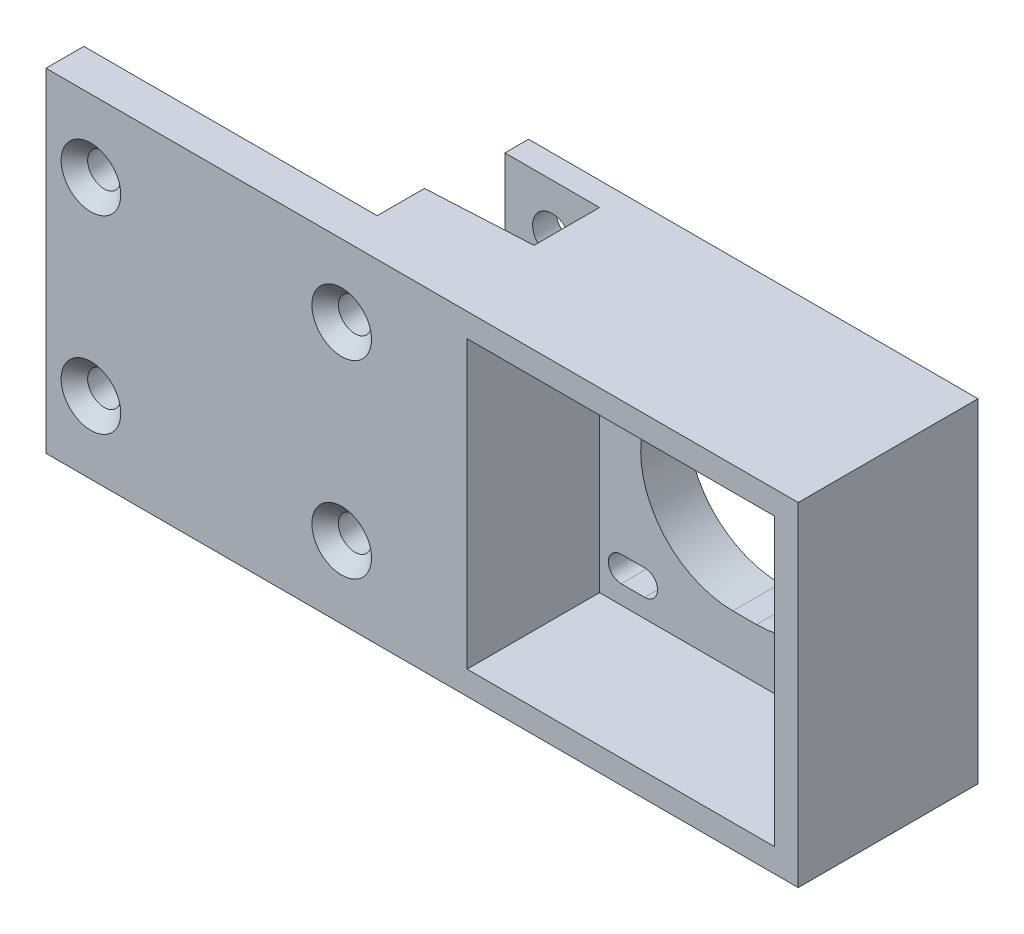
SolidWorks part; units mm, degrees
ref_plane "Front Plane" through (0, 0, 0) normal (0, 0, 1) x (1, 0, 0)
ref_plane "Top Plane" through (0, 0, 0) normal (0, 1, 0) x (1, 0, 0)
ref_plane "Right Plane" through (0, 0, 0) normal (1, 0, 0) x (0, 0, -1)
sketch "Sketch1" plane through (0, 0, 0) normal (0, 0, 1) x (1, 0, 0)
  line L1 (31, 106.401) -> (-31, 106.401) construction
  line L2 (31, 106.401) -> (31, 55.901) construction
  line L3 (31, 55.901) -> (-31, 55.901) construction
  line L4 (-31, 106.401) -> (-31, 55.901) construction
  line L5 (53, 116.401) -> (-36, 116.401)
  line L6 (53, 116.401) -> (53, 45.901)
  line L7 (53, 45.901) -> (-36, 45.901)
  line L8 (-36, 116.401) -> (-36, 45.901)
  circle A1 centre (26.5, 61.151) radius 2.5
  circle A2 centre (-26.5, 61.151) radius 2.5
  circle A3 centre (-26.5, 101.151) radius 2.5
  circle A4 centre (26.5, 101.151) radius 2.5
  dimension "D1" = 5
  dimension "D2" = 10
  dimension "D3" = 10
  dimension "D4" = 22
extrude "Boss-Extrude1" add sketch "Sketch1" along normal blind 8
sketch "Sketch2" plane through (53, 0, 0) normal (1, 0, 0) x (0, 0, -1)
  line L0 (-8, 45.901) -> (0, 45.901) construction
  line L1 (-8, 116.401) -> (30, 116.401)
  line L2 (-8, 116.401) -> (-8, 45.901)
  line L3 (-8, 45.901) -> (30, 45.901)
  line L4 (30, 116.401) -> (30, 45.901)
  dimension "D1" = 30
extrude "Boss-Extrude2" add sketch "Sketch2" against normal blind 5
sketch "Sketch3" plane through (0, 0, -30) normal (0, 0, -1) x (-1, 0, 0)
  line L0 (-48, 116.401) -> (-48, 45.901) construction
  line L1 (-53, 45.901) -> (-53, 116.401) construction
  line L2 (-48, 45.901) -> (-48, 116.401) construction
  line L3 (-48, 45.901) -> (-118, 45.901)
  line L4 (-48, 45.901) -> (-48, 116.401) construction
  line L5 (-48, 116.401) -> (-118, 116.401)
  line L6 (-118, 45.901) -> (-118, 116.401)
  line L7 (-53, 116.401) -> (36, 116.401) construction
  line L8 (-48, 116.401) -> (-28, 116.401)
  line L9 (-48, 116.401) -> (-48, 45.901) construction
  line L10 (-48, 45.901) -> (-28, 45.901)
  line L11 (-28, 116.401) -> (-28, 45.901)
  point P3 (-48, 81.151)
  point P7 (-48, 81.151)
  dimension "D2" = 65
  dimension "D3" = 20
extrude "Boss-Extrude3" add sketch "Sketch3" against normal blind 5
ref_plane "Plane1" through (0, 81.151, 0) normal (0, 1, 0) x (1, 0, 0)
sketch "Sketch17" plane through (0, 0, -25) normal (0, 0, 1) x (1, 0, 0)
  line L8 (118, 116.401) -> (53, 116.401)
  line L9 (118, 116.401) -> (53, 116.401)
  line L10 (53, 45.901) -> (118, 45.901)
  line L11 (53, 116.401) -> (53, 45.901)
  line L15 (53, 116.401) -> (53, 45.901)
  line L16 (53, 45.901) -> (118, 45.901)
  line L17 (118, 45.901) -> (118, 116.401)
  line L18 (118, 45.901) -> (118, 116.401)
  dimension "D1" = 0
extrude "Boss-Extrude6" add sketch "Sketch17" along normal blind 5
sketch "Sketch7" plane through (0, 0, -25) normal (0, 0, 1) x (1, 0, 0)
  line L0 (118, 81.151) -> (53, 81.151) construction
  line L1 (81.2, 100.651) -> (86.2, 100.651)
  line L2 (28, 45.901) -> (28, 116.401) construction
  line L3 (86.2, 61.651) -> (81.2, 61.651)
  line L4 (81.2, 81.151) -> (81.2, 104.781) construction
  line L6 (53, 45.901) -> (53, 116.401) construction
  line L7 (83.7, 71.0483) -> (83.7, 91.2537)
  line L8 (81.2, 104.781) -> (57.57, 104.781) construction
  line L9 (57.57, 107.481) -> (62.57, 107.481)
  line L10 (62.57, 102.081) -> (57.57, 102.081)
  line L11 (104.83, 102.081) -> (109.83, 102.081)
  line L12 (109.83, 107.481) -> (104.83, 107.481)
  line L13 (109.83, 54.821) -> (104.83, 54.821)
  line L14 (104.83, 60.221) -> (109.83, 60.221)
  line L15 (62.57, 60.221) -> (57.57, 60.221)
  line L16 (57.57, 54.821) -> (62.57, 54.821)
  line L17 (118, 45.901) -> (118, 116.401) construction
  circle A0 centre (38, 106.151) radius 4.15
  circle A1 centre (38, 56.151) radius 4.15
  circle A2 centre (81.2, 81.151) radius 19.5
  circle A3 centre (86.2, 81.151) radius 19.5
  arc A4 (57.57, 107.481) -> (57.57, 102.081) centre (57.57, 104.781) ccw
  arc A5 (62.57, 107.481) -> (62.57, 102.081) centre (62.57, 104.781) cw
  arc A6 (104.83, 107.481) -> (104.83, 102.081) centre (104.83, 104.781) ccw
  arc A7 (109.83, 107.481) -> (109.83, 102.081) centre (109.83, 104.781) cw
  arc A8 (109.83, 54.821) -> (109.83, 60.221) centre (109.83, 57.521) ccw
  arc A9 (104.83, 54.821) -> (104.83, 60.221) centre (104.83, 57.521) cw
  arc A10 (62.57, 54.821) -> (62.57, 60.221) centre (62.57, 57.521) ccw
  arc A11 (57.57, 54.821) -> (57.57, 60.221) centre (57.57, 57.521) cw
  point P10 (109.4, 81.151)
  point P19 (83.7, 81.151)
  dimension "D1" = 8.3
  dimension "D4" = 39
  dimension "D5" = 28.2
  dimension "D10" = 2.7
  dimension "D2" = 10
  dimension "D3" = 25
  dimension "D6" = 56.4
  dimension "D7" = 5
  dimension "D8" = 23.63
  dimension "D9" = 23.63
extrude "Cut-Extrude1" cut sketch "Sketch7" against normal up to next and the other way up to surface
sketch "Sketch8" plane through (0, 0, 8) normal (0, 0, 1) x (1, 0, 0)
  line L0 (26.5, 101.151) -> (26.5, 61.151) construction
  line L1 (26.5, 81.151) -> (-26.5, 81.151) construction
  line L2 (-26.5, 101.151) -> (-26.5, 61.151) construction
  line L3 (0, 104.6159) -> (0, 57.6861) construction
  line L4 (-23, 81.151) -> (23, 81.151) construction
  line L5 (-25, 56.151) -> (-25, 106.151)
  line L6 (-23, 58.151) -> (23, 58.151)
  line L7 (-23, 58.151) -> (-23, 104.151)
  line L8 (-23, 104.151) -> (23, 104.151)
  line L9 (23, 58.151) -> (23, 104.151)
  line L10 (-23, 58.151) -> (23, 104.151) construction
  line L11 (-23, 104.151) -> (23, 58.151) construction
  line L12 (-25, 106.151) -> (25, 106.151)
  line L13 (25, 56.151) -> (25, 106.151)
  line L14 (-25, 56.151) -> (25, 56.151)
  line L15 (0, 106.151) -> (0, 104.151)
  line L16 (0, 58.151) -> (0, 56.151)
  line L18 (-23, 85.901) -> (-20, 85.901)
  line L19 (-23, 85.901) -> (-23, 76.401)
  line L20 (-23, 76.401) -> (-20, 76.401)
  line L21 (-20, 85.901) -> (-20, 76.401)
  point P10 (0, 81.151)
  point P14 (0, 81.151)
  point P17 (0, 81.151)
  point P34 (-20, 81.151)
  dimension "D1" = 46
  dimension "D2" = 46
  dimension "D4" = 23
  dimension "D5" = 23
  dimension "D6" = 9.5
  dimension "D7" = 3
  dimension "D3" = 2
extrude "Boss-Extrude4" [suppressed] add sketch "Sketch8" along normal blind 50
ref_plane "Plane2" [suppressed] through (0, 81.151, 0) normal (0, -1, 0) x (-1, 0, 0)
sketch "Sketch9" [suppressed] plane through (0, 81.151, 0) normal (0, -1, 0) x (-1, 0, 0)
  line L0 (25, -58) -> (36, -8)
rib "Rib2" [suppressed] sketch "Sketch9" sketch "Sketch9" thickness 5 extrusion direction parallel to sketch draft on no parameters "D1"=5
ref_plane "Plane3" [suppressed] through (-12.5, 0, 0) normal (1, 0, 0) x (0, 0, -1)
sketch "Sketch11" [suppressed] plane through (0, 0, 0) normal (1, 0, 0) x (0, 0, -1)
  line L0 (-58, 106.151) -> (-8, 116.401)
rib "Rib4" [suppressed] sketch "Sketch11" sketch "Sketch11" thickness 5 extrusion direction parallel to sketch draft on no parameters "D1"=5
mirror "Mirror2" [suppressed] about plane through (0, 81.151, 0) normal (0, -1, 0)
sketch "Sketch12" [suppressed] plane through (-25, 0, 0) normal (-1, 0, 0) x (0, 0, 1)
  line L0 (58, 106.151) -> (8, 106.151) construction
  line L1 (8, 83.651) -> (8, 99.151) construction
  line L2 (38, 106.151) -> (8, 106.151)
  line L3 (8, 106.151) -> (8, 94.151)
  ellipse E0 centre (8, 106.151) end of major axis (38, 106.151) minor radius 12 (8, 94.151) -> (38, 106.151) ccw
  dimension "D1" = 30
  dimension "D2" = 12
extrude "Cut-Extrude2" [suppressed] cut sketch "Sketch12" against normal blind 5
mirror "Mirror3" [suppressed] about plane through (0, 81.151, 0) normal (0, -1, 0)
sketch "Sketch13" plane through (0, 0, 8) normal (0, 0, 1) x (1, 0, 0)
  point P0 (-26.5, 101.151)
  point P1 (-26.5, 61.151)
  point P3 (26.5, 61.151)
  point P5 (26.5, 101.151)
hole_wizard "CSK for M6 Countersunk Flat Head Screw1" positions "Sketch13" profile "Sketch14" countersink size "M6" standard "ISO"
sketch "Sketch14" plane through (-26.5, 101.151, 8) normal (1, 0, 0) x (0, -1, 0)
  line L0 (0, 0) -> (0, 10.103)
  line L1 (0, 10.103) -> (3.5, 8)
  line L2 (3.5, 8) -> (3.5, 2.8)
  line L3 (3.5, 2.8) -> (6.3, 0)
  line L5 (6.3, 0) -> (0, 0)
  line L6 (-3.5, 2.8) -> (-6.3, 0) construction
  line L10 (0, 10.103) -> (-3.5, 8) construction
  line L11 (0, -6.35) -> (0, 107.95) construction
  dimension "Hole Dia." = 7
  dimension "Hole Depth" = 8
  dimension "Near C'Sink Dia." = 12.6
  dimension "Near C'Sink Angle" = 90
  dimension "Drill Angle" = 118
sketch "Sketch15" plane through (0, 81.151, 0) normal (0, 1, 0) x (1, 0, 0)
  line L0 (34, 25) -> (34, 0)
  line L1 (53, 0) -> (-36, 0) construction
  line L2 (28, 25) -> (48, 25) construction
  line L3 (53, 0) -> (-36, 0) construction
  line L4 (48, 25) -> (48, 0) construction
  dimension "D1" = 14
rib "Rib5" sketch "Sketch15" sketch "Sketch15" thickness 5 extrusion direction parallel to sketch draft on yes draft angle 20 parameters "D1"=5, "D3"=20
sketch "Sketch16" plane through (0, 45.901, 0) normal (0, -1, 0) x (1, 0, 0)
  line L0 (-36, 8) -> (53, 8) construction
  line L1 (118, -30) -> (123, -30)
  line L2 (118, -30) -> (118, 8)
  line L3 (118, 8) -> (123, 8)
  line L4 (123, -30) -> (123, 8)
  dimension "D1" = 5
extrude "Boss-Extrude5" add sketch "Sketch16" against normal up to surface (70.5 mm away) up to face at (42.2, 116.401, -13.4)
sketch "Sketch6" plane through (0, 116.401, 0) normal (0, 1, 0) x (1, 0, 0)
  line L0 (53, -8) -> (118, -8)
rib "Rib1" sketch "Sketch6" sketch "Sketch6" thickness 5 extrusion direction parallel to sketch draft on no parameters "D1"=5
sketch "Sketch19" plane through (0, 116.401, 0) normal (0, 1, 0) x (1, 0, 0)
  line L0 (48, 10) -> (26, 10)
  line L1 (48, 25) -> (48, 0) construction
  line L2 (26, 10) -> (26, 0)
  line L3 (26, 0) -> (48, 0)
  line L4 (48, 0) -> (48, 10)
  line L5 (48, 0) -> (-36, 0) construction
  line L6 (26, 10) -> (48, 11.153)
  line L7 (48, 11.153) -> (48, 10)
  line M10 (48, 25) -> (48, 0)
  line M11 (48, 0) -> (-36, 0)
  dimension "D1" = 10
  dimension "D2" = 22
  dimension "D3" = 3
extrude "Boss-Extrude7" add sketch "Sketch19" against normal blind 7 contours L0 L2 M11 M10 | L6 L0 M10
mirror "Mirror5" about plane through (0, 81.151, 0) normal (0, 1, 0) of "Rib1"
mirror "Mirror6" about plane through (0, 81.151, 0) normal (0, 1, 0) of "Boss-Extrude7"
sketch "Sketch20" plane through (28, 0, 0) normal (-1, 0, 0) x (0, 0, 1)
  line L0 (-25, 45.901) -> (-25, 116.401) construction
  line L1 (-25, 30.901) -> (-55, 30.901)
  line L2 (-25, 30.901) -> (-25, 131.401)
  line L3 (-25, 131.401) -> (-55, 131.401)
  line L4 (-55, 30.901) -> (-55, 131.401)
  line L5 (-25, 45.901) -> (-30, 45.901) construction
  line L6 (-25, 116.401) -> (-30, 116.401) construction
  line L7 (-30, 45.901) -> (-30, 116.401) construction
  line L8 (-30, 37.901) -> (-51, 37.901)
  line L9 (-30, 37.901) -> (-30, 124.401)
  line L10 (-30, 124.401) -> (-51, 124.401)
  line L11 (-51, 37.901) -> (-51, 124.401)
  point P8 (-27.5, 45.901)
  dimension "D1" = 15
  dimension "D2" = 15
  dimension "D3" = 30
  dimension "D4" = 8
  dimension "D5" = 8
  dimension "D6" = 4
extrude "Boss-Extrude8" [suppressed] add sketch "Sketch20" along normal blind 7
fillet "Fillet1" radius 2.5 12 edges at (48, 88.7466, -12.5) (48, 73.5554, -12.5) (34, 83.651, -12.5) (41, 86.1988, 0) (34, 81.151, 0) (41, 76.1032, 0) (41, 76.1032, -25) (41, 86.1988, -25) (34, 78.651, -12.5) (34, 81.151, -25) (48, 63.2282, 0) (48, 99.0738, 0)
fillet "Fillet2" [suppressed] radius 2.5
fillet "Fillet3" [suppressed] radius 2.5
